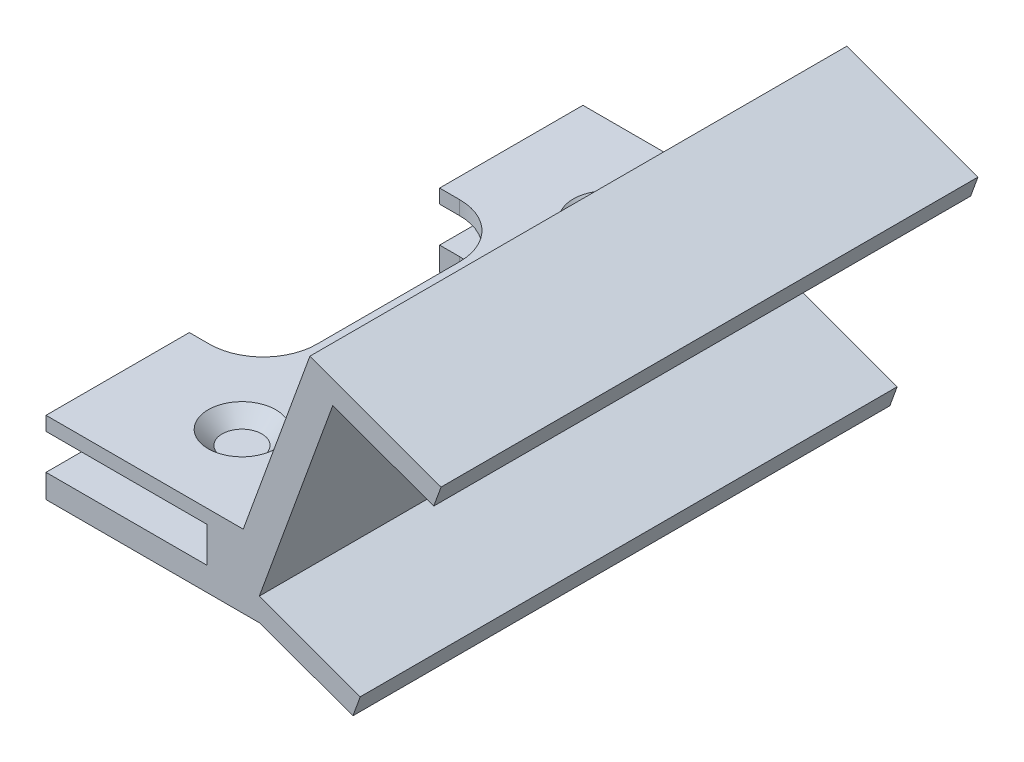
SolidWorks part; units mm, degrees
material "ABS"
ref_plane "Front Plane" through (0, 0, 0) normal (0, 0, 1) x (1, 0, 0)
ref_plane "Top Plane" through (0, 0, 0) normal (0, 1, 0) x (1, 0, 0)
ref_plane "Right Plane" through (0, 0, 0) normal (1, 0, 0) x (0, 0, -1)
sketch "Sketch1" plane through (0, 0, 0) normal (0, 0, 1) x (1, 0, 0)
  line L12 (10.8862, 19.4408) -> (30.8204, 19.4408)
  line L31 (30.8204, 19.4408) -> (39.4657, 16.2942)
  line L32 (39.4657, 16.2942) -> (40.1498, 18.1736)
  line L33 (40.1498, 18.1736) -> (30.7529, 21.5938)
  line L34 (30.7529, 21.5938) -> (37.5933, 40.3876)
  line L35 (37.5933, 40.3876) -> (46.9902, 36.9674)
  line L36 (46.9902, 36.9674) -> (47.6742, 38.8468)
  line L37 (47.6742, 38.8468) -> (35.4582, 43.2931)
  line L38 (35.4582, 43.2931) -> (29.2517, 26.2408)
  line L40 (25.8862, 24.9408) -> (25.8862, 21.6408)
  line L41 (25.8862, 24.9408) -> (10.8862, 24.9408)
  line L42 (10.8862, 21.6408) -> (25.8862, 21.6408)
  line L43 (29.2517, 26.2408) -> (10.8862, 26.2408)
  line L44 (10.8862, 26.2408) -> (10.8862, 24.9408)
  line L45 (10.8862, 21.6408) -> (10.8862, 19.4408)
  dimension "D1" = 2
  dimension "D2" = 20
  dimension "D3" = 3
  dimension "D4" = 10
  dimension "D5" = 4.9342
  dimension "D6" = 15
  dimension "D7" = 3.3
  dimension "D8" = 160
  dimension "D9" = 1.3
extrude "DampingBracketGeometry" add sketch "Sketch1" along normal blind 50
hole_wizard "CSK for M3 Flat Head Machine Screw1" positions "Sketch3" profile "Sketch4" countersink size "M3" standard "ANSI Metric" end condition through all
sketch "Sketch3" plane through (0, 26.2408, 0) normal (0, 1, 0) x (1, 0, 0)
  line L13 (25.7717, 0) -> (25.7717, -50) construction
  line L16 (21.1362, -42) -> (25.7717, -42) construction
  line L18 (21.1362, -8) -> (25.7717, -8) construction
  line L20 (29.2517, -50) -> (29.2517, 0) construction
  line L21 (21.1362, -8) -> (21.1362, 0) construction
  line L22 (29.2517, 0) -> (10.8862, 0) construction
  line L24 (21.1362, -42) -> (21.1362, -50) construction
  line L25 (29.2517, -50) -> (10.8862, -50) construction
  point P0 (21.1362, -8)
  point P2 (21.1362, -42)
  dimension "D1" = 3.48
  dimension "D2" = 8
  dimension "D3" = 4.75
sketch "Sketch4" plane through (21.1362, 26.2408, 8) normal (1, 0, 0) x (0, 0, 1)
  line L0 (0, 0) -> (0, 9.9467)
  line L1 (0, 9.9467) -> (1.7, 9.9467)
  line L2 (1.7, 9.9467) -> (1.7, 1.45)
  line L3 (1.7, 1.45) -> (3.15, 0)
  line L5 (3.15, 0) -> (0, 0)
  line L6 (-1.7, 1.45) -> (-3.15, 0) construction
  line L11 (0, -6.35) -> (0, 107.95) construction
  dimension "Thru Hole Dia." = 3.4
  dimension "Thru Hole Depth" = 9.9467
  dimension "Near C'Sink Dia." = 6.3
  dimension "Near C'Sink Angle" = 90
sketch "Sketch5" plane through (0, 26.2408, 0) normal (0, 1, 0) x (1, 0, 0)
  line L0 (10.8862, -50) -> (10.8862, 0) construction
  line L1 (4.0112, -13.3476) -> (17.7612, -13.3476)
  line L2 (4.0112, -13.3476) -> (4.0112, -36.6524)
  line L3 (4.0112, -36.6524) -> (17.7612, -36.6524)
  line L4 (17.7612, -13.3476) -> (17.7612, -36.6524)
  line L5 (4.0112, -13.3476) -> (17.7612, -36.6524) construction
  line L6 (4.0112, -36.6524) -> (17.7612, -13.3476) construction
  point P0 (10.8862, -25)
  dimension "D1" = 13.75
extrude "Cut-Extrude1" cut sketch "Sketch5" against normal through all
fillet "Fillet1" radius 5 4 edges at (17.7612, 20.5408, 36.6524) (17.7612, 25.5908, 36.6524) (17.7612, 20.5408, 13.3476) (17.7612, 25.5908, 13.3476)
